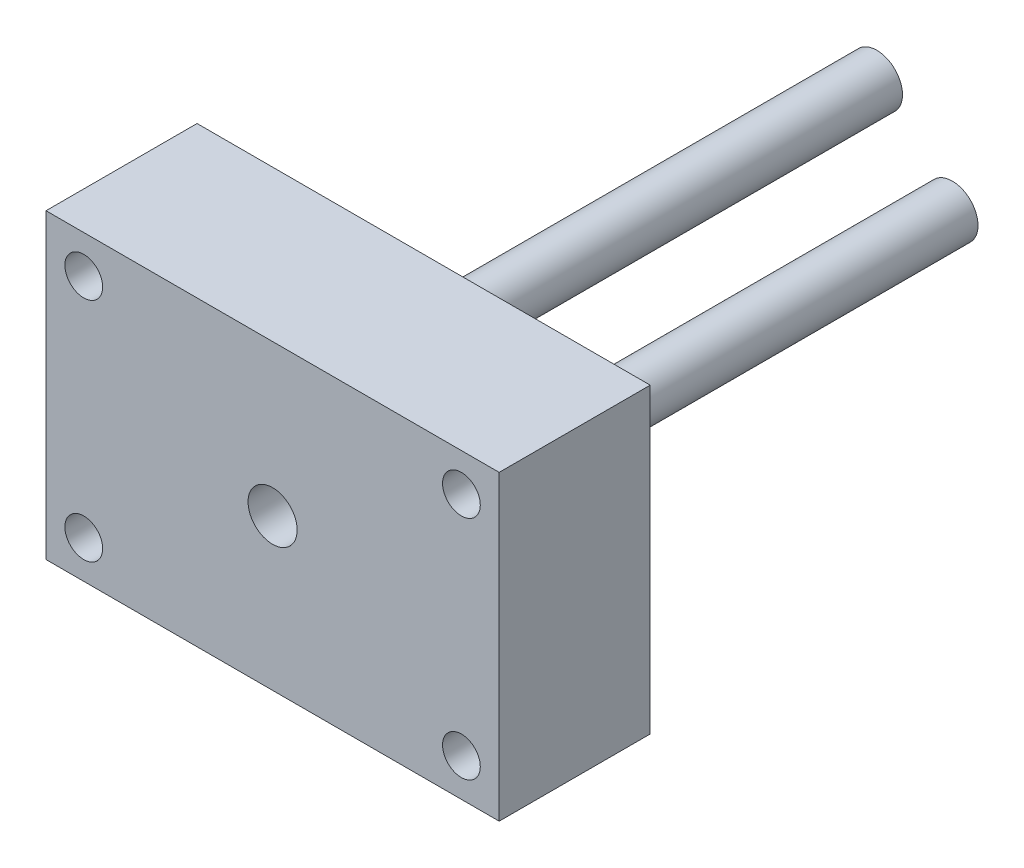
SolidWorks part; units mm, degrees
ref_plane "Front Plane" through (0, 0, 0) normal (0, 0, 1) x (1, 0, 0)
ref_plane "Top Plane" through (0, 0, 0) normal (0, 1, 0) x (1, 0, 0)
ref_plane "Right Plane" through (0, 0, 0) normal (1, 0, 0) x (0, 0, -1)
sketch "Sketch1" plane through (0, 0, 0) normal (0, 0, 1) x (1, 0, 0)
  line L0 (38.1, 25.4) -> (38.1, 38.1) construction
  line L1 (0, 0) -> (76.2, 0)
  line L2 (0, 0) -> (0, 50.8)
  line L3 (0, 50.8) -> (76.2, 50.8)
  line L4 (76.2, 0) -> (76.2, 50.8)
  circle A0 centre (38.1, 38.1) radius 4.3137
  circle A1 centre (50.8, 25.4) radius 4.3137
  circle A2 centre (38.1, 12.7) radius 4.3137
  circle A3 centre (25.4, 25.4) radius 4.3137
  point P7 (38.1, 26.031)
  dimension "D1" = 76.2
  dimension "D2" = 50.8
  dimension "D4" = 12.7
  dimension "D3" = 4
sketch "Sketch4" plane through (0, 0, 0) normal (0, 0, 1) x (1, 0, 0)
  circle A0 centre (38.1, 38.1) radius 4.3137
extrude "Boss-Extrude2" add sketch "Sketch1" along normal blind 25.4
sketch "Sketch6" plane through (0, 0, 25.4) normal (0, 0, 1) x (1, 0, 0)
  circle A0 centre (38.1, 25.4) radius 4.1275
  circle A1 centre (6.35, 44.45) radius 3.175
  circle A2 centre (69.85, 44.45) radius 3.175
  circle A3 centre (6.35, 6.35) radius 3.175
  circle A4 centre (69.85, 6.35) radius 3.175
  dimension "D1" = 2
  dimension "D2" = 2
  dimension "D3" = 2
extrude "Cut-Extrude3" cut sketch "Sketch6" against normal blind 25.4
sketch "Sketch7" plane through (0, 0, 25.4) normal (0, 0, 1) x (1, 0, 0)
  circle A2 centre (25.4, 25.4) radius 4.3137
extrude "Boss-Extrude3" add sketch "Sketch7" against normal blind 101.6 contours A2
sketch "Sketch9" plane through (0, 0, 25.4) normal (0, 0, 1) x (1, 0, 0)
  circle A0 centre (50.8, 25.4) radius 4.3137
extrude "Boss-Extrude5" add sketch "Sketch9" against normal blind 101.6
sketch "Sketch11" plane through (0, 0, 25.4) normal (0, 0, 1) x (1, 0, 0)
  circle A0 centre (38.0978, 38.1013) radius 4.3162
extrude "Boss-Extrude6" add sketch "Sketch11" against normal blind 101.6
sketch "Sketch14" plane through (0, 0, 25.4) normal (0, 0, 1) x (1, 0, 0)
  circle A0 centre (38.1, 12.7) radius 4.3137
extrude "Boss-Extrude7" add sketch "Sketch14" against normal blind 101.6
